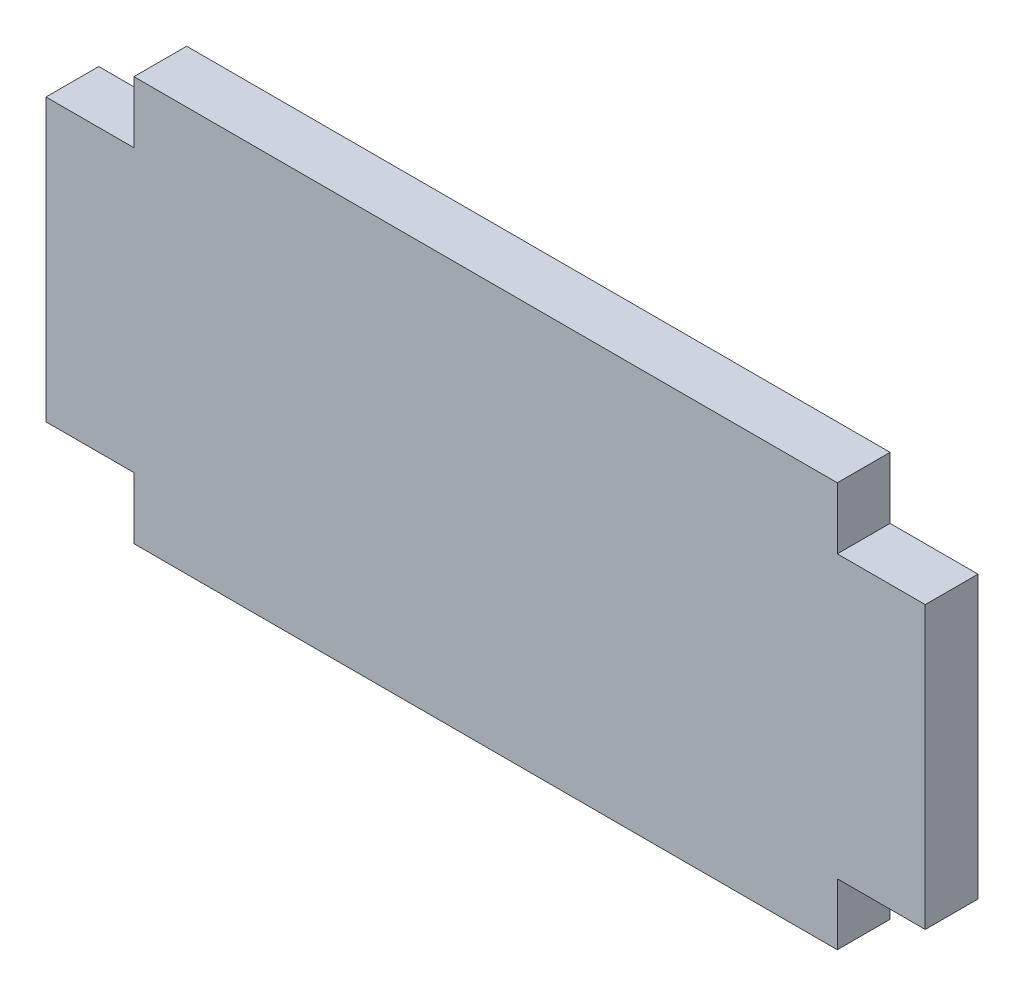
SolidWorks part; units mm, degrees
material "Hêtre"
ref_plane "Plan de face" through (0, 0, 0) normal (0, 0, 1) x (1, 0, 0)
ref_plane "Plan de dessus" through (0, 0, 0) normal (0, 1, 0) x (1, 0, 0)
ref_plane "Plan de droite" through (0, 0, 0) normal (1, 0, 0) x (0, 0, -1)
sketch "Esquisse1" plane through (0, 0, 0) normal (0, 0, 1) x (1, 0, 0)
  line L0 (-4, -16) -> (-4, 16)
  line L1 (-4, -16) -> (6, -16)
  line L2 (6, -16) -> (6, -23)
  line L4 (6, -23) -> (86, -23)
  line L7 (46, 29.9608) -> (46, -31.1493) construction
  line L8 (-20.0623, 0) -> (112.3595, 0) construction
  line L9 (86, -16) -> (86, -23)
  line L10 (96, -16) -> (86, -16)
  line L11 (96, -16) -> (96, 16)
  line L12 (96, 16) -> (86, 16)
  line L13 (86, 16) -> (86, 23)
  line L14 (6, 23) -> (86, 23)
  line L15 (6, 16) -> (6, 23)
  line L16 (-4, 16) -> (6, 16)
  point P0 (46, 23)
  point P19 (46, -23)
  point P23 (96, 0)
  point P28 (-4, 0)
extrude "Boss.-Extru.1" add sketch "Esquisse1" along normal blind 6
